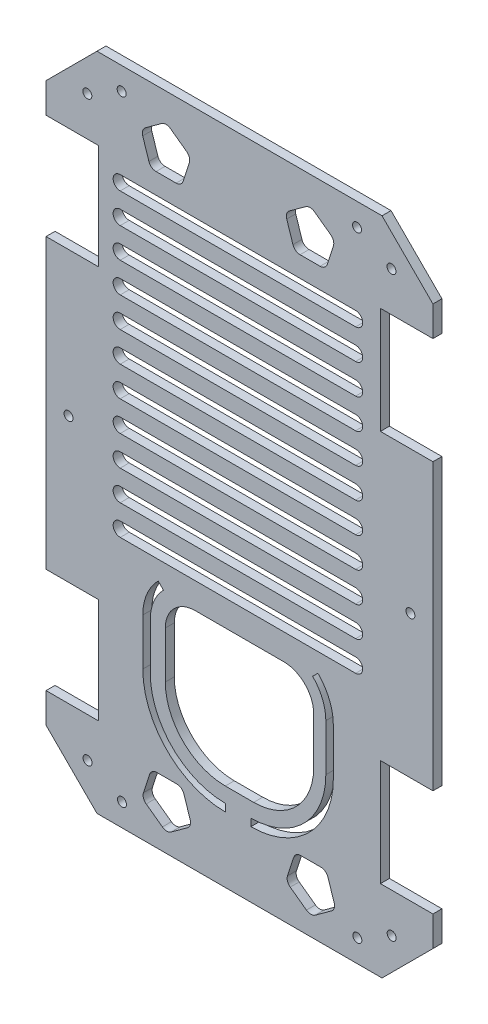
SolidWorks part; units mm, degrees
material "PE High Density"
ref_plane "Front Plane" through (0, 0, 0) normal (0, 0, 1) x (1, 0, 0)
ref_plane "Top Plane" through (0, 0, 0) normal (0, 1, 0) x (1, 0, 0)
ref_plane "Right Plane" through (0, 0, 0) normal (1, 0, 0) x (0, 0, -1)
sketch "Sketch1" plane through (0, 0, 0) normal (0, 0, 1) x (1, 0, 0)
  line L0 (-95, 220) -> (-128.9411, 186.0589)
  line L1 (-128.9411, 186.0589) -> (-128.9411, 166.0589)
  line L2 (-128.9411, 166.0589) -> (-93.9411, 166.0589)
  line L3 (-93.9411, 166.0589) -> (-93.9411, 96.0589)
  line L4 (-93.9411, 96.0589) -> (-128.9411, 96.0589)
  line L5 (-128.9411, 96.0589) -> (-128.9411, -96.0589)
  line L6 (-128.9411, -96.0589) -> (-93.9411, -96.0589)
  line L7 (-93.9411, -96.0589) -> (-93.9411, -166.0589)
  line L8 (-93.9411, -166.0589) -> (-128.9411, -166.0589)
  line L9 (-128.9411, -166.0589) -> (-128.9411, -186.0589)
  line L10 (-128.9411, -186.0589) -> (-95, -220)
  line L11 (-95, -220) -> (95, -220)
  line L12 (95, -220) -> (128.9411, -186.0589)
  line L13 (128.9411, -186.0589) -> (128.9411, -166.0589)
  line L14 (128.9411, -166.0589) -> (93.9411, -166.0589)
  line L15 (93.9411, -166.0589) -> (93.9411, -95)
  line L16 (93.9411, -95) -> (128.9411, -95)
  line L17 (128.9411, -95) -> (128.9411, 95)
  line L18 (128.9411, 95) -> (93.9411, 95)
  line L19 (93.9411, 95) -> (93.9411, 166.0589)
  line L20 (93.9411, 166.0589) -> (128.9411, 166.0589)
  line L21 (128.9411, 166.0589) -> (128.9411, 186.0589)
  line L22 (128.9411, 186.0589) -> (95, 220)
  line L23 (95, 220) -> (-95, 220)
  line L24 (-79.511, 151.815) -> (77.389, 151.815) construction
  line L25 (-29.457, -70.183) -> (29.457, -70.183)
  line L26 (-49.457, -90.183) -> (-49.457, -121.3896)
  line L27 (-9.457, -161.3896) -> (9.457, -161.3896)
  line L28 (49.457, -90.183) -> (49.457, -121.3896)
  line L29 (-79.511, 156.535) -> (77.389, 156.535)
  line L30 (-79.511, 147.0951) -> (77.389, 147.0951)
  line L31 (-79.511, 131.815) -> (77.389, 131.815) construction
  line L32 (-79.511, 136.535) -> (77.389, 136.535)
  line L33 (-79.511, 127.0951) -> (77.389, 127.0951)
  line L34 (-79.511, 111.815) -> (77.389, 111.815) construction
  line L35 (-79.511, 116.535) -> (77.389, 116.535)
  line L36 (-79.511, 107.0951) -> (77.389, 107.0951)
  line L37 (-79.511, 91.815) -> (77.389, 91.815) construction
  line L38 (-79.511, 96.535) -> (77.389, 96.535)
  line L39 (-79.511, 87.0951) -> (77.389, 87.0951)
  line L40 (-79.511, 71.815) -> (77.389, 71.815) construction
  line L41 (-79.511, 76.535) -> (77.389, 76.535)
  line L42 (-79.511, 67.0951) -> (77.389, 67.0951)
  line L43 (-45.5181, -205.9768) -> (-34.7185, -198.1304)
  line L44 (-32.9021, -192.5403) -> (-37.0272, -179.8445)
  line L45 (-41.7825, -176.3896) -> (-55.1316, -176.3896)
  line L46 (-59.8868, -179.8445) -> (-64.0119, -192.5403)
  line L47 (-62.1956, -198.1304) -> (-51.3959, -205.9768)
  line L48 (-79.511, 51.815) -> (77.389, 51.815) construction
  line L49 (61.2815, -198.1304) -> (50.4819, -205.9768)
  line L50 (58.9728, -179.8445) -> (63.0979, -192.5403)
  line L51 (40.8684, -176.3896) -> (54.2175, -176.3896)
  line L52 (31.9881, -192.5403) -> (36.1132, -179.8445)
  line L53 (44.6041, -205.9768) -> (33.8044, -198.1304)
  line L54 (-79.511, 56.535) -> (77.389, 56.535)
  line L55 (-79.511, 47.0951) -> (77.389, 47.0951)
  line L56 (-79.511, 31.815) -> (77.389, 31.815) construction
  line L57 (-79.511, 36.535) -> (77.389, 36.535)
  line L58 (-79.511, 27.0951) -> (77.389, 27.0951)
  line L59 (-79.511, 11.815) -> (77.389, 11.815) construction
  line L60 (-79.511, 16.535) -> (77.389, 16.535)
  line L61 (-79.511, 7.0951) -> (77.389, 7.0951)
  line L62 (-79.511, -8.185) -> (77.389, -8.185) construction
  line L63 (44.1041, 199.8098) -> (33.3044, 191.9634)
  line L64 (31.4881, 186.3732) -> (35.6132, 173.6775)
  line L65 (40.3684, 170.2226) -> (53.7175, 170.2226)
  line L66 (58.4728, 173.6775) -> (62.5979, 186.3732)
  line L67 (60.7815, 191.9634) -> (49.9819, 199.8098)
  line L68 (-62.6956, 191.9634) -> (-51.8959, 199.8098)
  line L69 (-60.3868, 173.6775) -> (-64.5119, 186.3732)
  line L70 (-42.2825, 170.2226) -> (-55.6316, 170.2226)
  line L71 (-33.4021, 186.3732) -> (-37.5272, 173.6775)
  line L72 (-46.0181, 199.8098) -> (-35.2185, 191.9634)
  line L73 (-79.511, -3.465) -> (77.389, -3.465)
  line L74 (-79.511, -12.9049) -> (77.389, -12.9049)
  line L75 (-79.511, -28.185) -> (77.389, -28.185) construction
  line L76 (-79.511, -23.465) -> (77.389, -23.465)
  line L77 (-79.511, -32.9049) -> (77.389, -32.9049)
  line L78 (-79.511, -48.185) -> (77.389, -48.185) construction
  line L79 (-79.511, -43.465) -> (77.389, -43.465)
  line L80 (-79.511, -52.9049) -> (77.389, -52.9049)
  line L81 (-59.457, -90.183) -> (-59.457, -121.3896)
  line L82 (-9.457, -171.3896) -> (-9.457, -176.3896)
  line L83 (-64.457, -90.183) -> (-64.457, -121.3896)
  line L84 (-50.6702, -68.9698) -> (-54.2058, -65.4343)
  line L85 (48.7562, -68.9698) -> (52.2917, -65.4343)
  line L86 (57.543, -90.183) -> (57.543, -121.3896)
  line L87 (62.543, -90.183) -> (62.543, -121.3896)
  line L88 (7.543, -171.3896) -> (7.543, -176.3896)
  circle A0 centre (-101.294, -192.4928) radius 3
  circle A1 centre (-78.554, 205) radius 3
  circle A2 centre (-113.9411, 0) radius 3
  circle A3 centre (-78.346, -205) radius 3
  circle A4 centre (78.554, -205) radius 3
  circle A5 centre (101.4339, -192.3529) radius 3
  circle A6 centre (113.9411, 0) radius 3
  circle A7 centre (101.294, 192.4928) radius 3
  circle A8 centre (78.346, 205) radius 3
  circle A9 centre (-101.4339, 192.3529) radius 3
  arc A10 (-49.457, -90.183) -> (-29.457, -70.183) centre (-29.457, -90.183) cw
  arc A11 (49.457, -90.183) -> (29.457, -70.183) centre (29.457, -90.183) ccw
  arc A12 (-9.457, -161.3896) -> (-49.457, -121.3896) centre (-9.457, -121.3896) cw
  arc A13 (9.457, -161.3896) -> (49.457, -121.3896) centre (9.457, -121.3896) ccw
  arc A14 (35.6132, 173.6775) -> (40.3684, 170.2226) centre (40.3684, 175.2226) ccw
  arc A15 (53.7175, 170.2226) -> (58.4728, 173.6775) centre (53.7175, 175.2226) ccw
  arc A16 (62.5979, 186.3732) -> (60.7815, 191.9634) centre (57.8426, 187.9183) ccw
  arc A17 (49.9819, 199.8098) -> (44.1041, 199.8098) centre (47.043, 195.7647) ccw
  arc A18 (33.3044, 191.9634) -> (31.4881, 186.3732) centre (36.2434, 187.9183) ccw
  arc A19 (-62.6956, 191.9634) -> (-64.5119, 186.3732) centre (-59.7566, 187.9183) ccw
  arc A20 (-60.3868, 173.6775) -> (-55.6316, 170.2226) centre (-55.6316, 175.2226) ccw
  arc A21 (-42.2825, 170.2226) -> (-37.5272, 173.6775) centre (-42.2825, 175.2226) ccw
  arc A22 (-33.4021, 186.3732) -> (-35.2185, 191.9634) centre (-38.1574, 187.9183) ccw
  arc A23 (-46.0181, 199.8098) -> (-51.8959, 199.8098) centre (-48.957, 195.7647) ccw
  arc A24 (-37.0272, -179.8445) -> (-41.7825, -176.3896) centre (-41.7825, -181.3896) ccw
  arc A25 (-55.1316, -176.3896) -> (-59.8868, -179.8445) centre (-55.1316, -181.3896) ccw
  arc A26 (-64.0119, -192.5403) -> (-62.1956, -198.1304) centre (-59.2566, -194.0853) ccw
  arc A27 (-51.3959, -205.9768) -> (-45.5181, -205.9768) centre (-48.457, -201.9317) ccw
  arc A28 (-34.7185, -198.1304) -> (-32.9021, -192.5403) centre (-37.6574, -194.0853) ccw
  arc A29 (61.2815, -198.1304) -> (63.0979, -192.5403) centre (58.3426, -194.0853) ccw
  arc A30 (54.2175, -176.3896) -> (58.9728, -179.8445) centre (54.2175, -181.3896) cw
  arc A31 (36.1132, -179.8445) -> (40.8684, -176.3896) centre (40.8684, -181.3896) cw
  arc A32 (31.9881, -192.5403) -> (33.8044, -198.1304) centre (36.7434, -194.0853) ccw
  arc A33 (44.6041, -205.9768) -> (50.4819, -205.9768) centre (47.543, -201.9317) ccw
  arc A34 (-79.511, 156.535) -> (-79.511, 147.0951) centre (-79.511, 151.815) ccw
  arc A35 (77.389, 147.0951) -> (77.389, 156.535) centre (77.389, 151.815) ccw
  arc A36 (-79.511, 136.535) -> (-79.511, 127.0951) centre (-79.511, 131.815) ccw
  arc A37 (77.389, 127.0951) -> (77.389, 136.535) centre (77.389, 131.815) ccw
  arc A38 (-79.511, 116.535) -> (-79.511, 107.0951) centre (-79.511, 111.815) ccw
  arc A39 (77.389, 107.0951) -> (77.389, 116.535) centre (77.389, 111.815) ccw
  arc A40 (-79.511, 96.535) -> (-79.511, 87.0951) centre (-79.511, 91.815) ccw
  arc A41 (77.389, 87.0951) -> (77.389, 96.535) centre (77.389, 91.815) ccw
  arc A42 (-79.511, 76.535) -> (-79.511, 67.0951) centre (-79.511, 71.815) ccw
  arc A43 (77.389, 67.0951) -> (77.389, 76.535) centre (77.389, 71.815) ccw
  arc A44 (-79.511, 56.535) -> (-79.511, 47.0951) centre (-79.511, 51.815) ccw
  arc A45 (77.389, 47.0951) -> (77.389, 56.535) centre (77.389, 51.815) ccw
  arc A46 (-79.511, 36.535) -> (-79.511, 27.0951) centre (-79.511, 31.815) ccw
  arc A47 (77.389, 27.0951) -> (77.389, 36.535) centre (77.389, 31.815) ccw
  arc A48 (-79.511, 16.535) -> (-79.511, 7.0951) centre (-79.511, 11.815) ccw
  arc A49 (77.389, 7.0951) -> (77.389, 16.535) centre (77.389, 11.815) ccw
  arc A50 (-79.511, -3.465) -> (-79.511, -12.9049) centre (-79.511, -8.185) ccw
  arc A51 (77.389, -12.9049) -> (77.389, -3.465) centre (77.389, -8.185) ccw
  arc A52 (-79.511, -23.465) -> (-79.511, -32.9049) centre (-79.511, -28.185) ccw
  arc A53 (77.389, -32.9049) -> (77.389, -23.465) centre (77.389, -28.185) ccw
  arc A54 (-79.511, -43.465) -> (-79.511, -52.9049) centre (-79.511, -48.185) ccw
  arc A55 (77.389, -52.9049) -> (77.389, -43.465) centre (77.389, -48.185) ccw
  arc A56 (-9.457, -171.3896) -> (-59.457, -121.3896) centre (-9.457, -121.3896) cw
  arc A57 (-59.457, -90.183) -> (-50.6702, -68.9698) centre (-29.457, -90.183) cw
  arc A58 (-9.457, -176.3896) -> (-64.457, -121.3896) centre (-9.457, -121.3896) cw
  arc A59 (-64.457, -90.183) -> (-54.2058, -65.4343) centre (-29.457, -90.183) cw
  arc A60 (57.543, -90.183) -> (48.7562, -68.9698) centre (27.543, -90.183) ccw
  arc A61 (62.543, -90.183) -> (52.2917, -65.4343) centre (27.543, -90.183) ccw
  arc A62 (7.543, -176.3896) -> (62.543, -121.3896) centre (7.543, -121.3896) ccw
  arc A63 (7.543, -171.3896) -> (57.543, -121.3896) centre (7.543, -121.3896) ccw
  point P71 (-1.061, 151.815)
  point P80 (-1.061, 131.815)
  point P87 (-1.061, 111.815)
  point P94 (-1.061, 91.815)
  point P101 (-1.061, 71.815)
  point P108 (-1.061, 51.815)
  point P115 (-1.061, 31.815)
  point P122 (-1.061, 11.815)
  point P129 (-1.061, -8.185)
  point P136 (-1.061, -28.185)
  point P143 (-1.061, -48.185)
  point P184 (47.543, -70.183)
  point P206 (50.524, -67.2021)
  dimension "D1" = 5
extrude "Boss-Extrude1" add sketch "Sketch1" along normal blind 6
